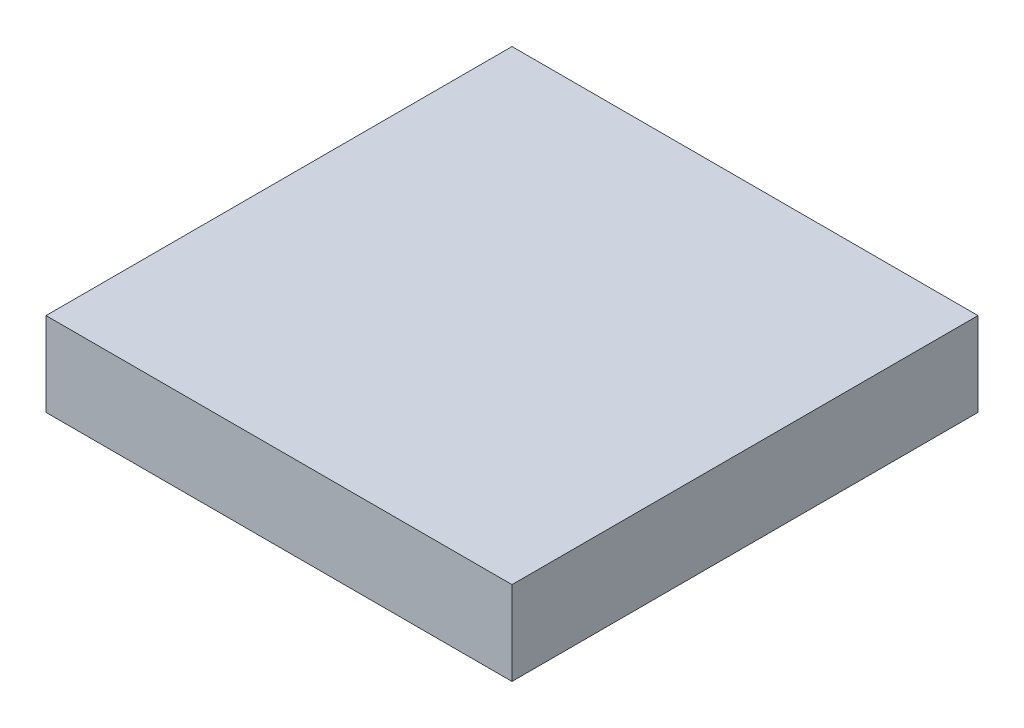
SolidWorks part; units mm, degrees
ref_plane "Ön Düzlem" through (0, 0, 0) normal (0, 0, 1) x (1, 0, 0)
ref_plane "Üst Düzlem" through (0, 0, 0) normal (0, 1, 0) x (1, 0, 0)
ref_plane "Sağ Düzlem" through (0, 0, 0) normal (1, 0, 0) x (0, 0, -1)
sketch "Çizim1" plane through (0, 0, 0) normal (0, 1, 0) x (1, 0, 0)
  line L1 (-5, 5) -> (5, 5)
  line L2 (-5, 5) -> (-5, -5)
  line L3 (-5, -5) -> (5, -5)
  line L4 (5, 5) -> (5, -5)
  line L5 (-5, 5) -> (5, -5) construction
  line L6 (-5, -5) -> (5, 5) construction
  point P0 (0, 0)
  dimension "D1" = 10
  dimension "D2" = 10
extrude "Yükseklik-Ekstrüzyon1" add sketch "Çizim1" along normal blind 1.8
